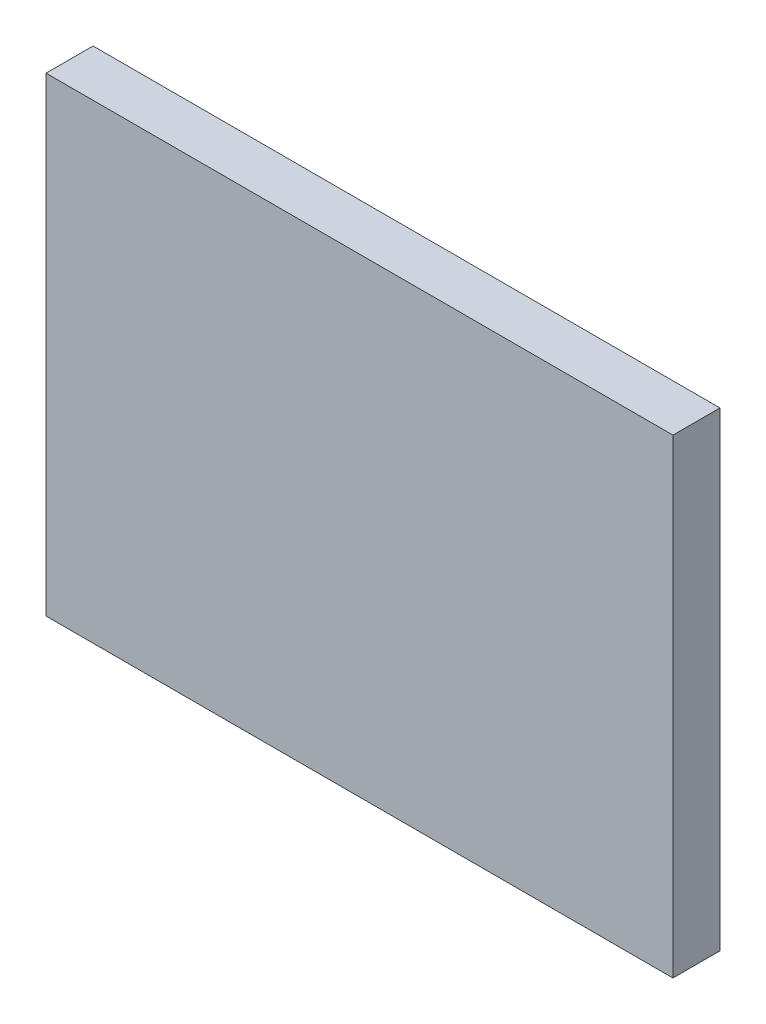
SolidWorks part; units mm, degrees
ref_plane "Спереди" through (0, 0, 0) normal (0, 0, 1) x (1, 0, 0)
ref_plane "Сверху" through (0, 0, 0) normal (0, 1, 0) x (1, 0, 0)
ref_plane "Справа" through (0, 0, 0) normal (1, 0, 0) x (0, 0, -1)
sketch "Эскиз1" plane through (0, 0, 0) normal (0, 0, 1) x (1, 0, 0)
  line L1 (0, 0) -> (40, 0)
  line L2 (0, 0) -> (0, 30)
  line L3 (0, 30) -> (40, 30)
  line L4 (40, 0) -> (40, 30)
  dimension "D1" = 30
  dimension "D2" = 40
extrude "Бобышка-Вытянуть1" add sketch "Эскиз1" along normal blind 3
